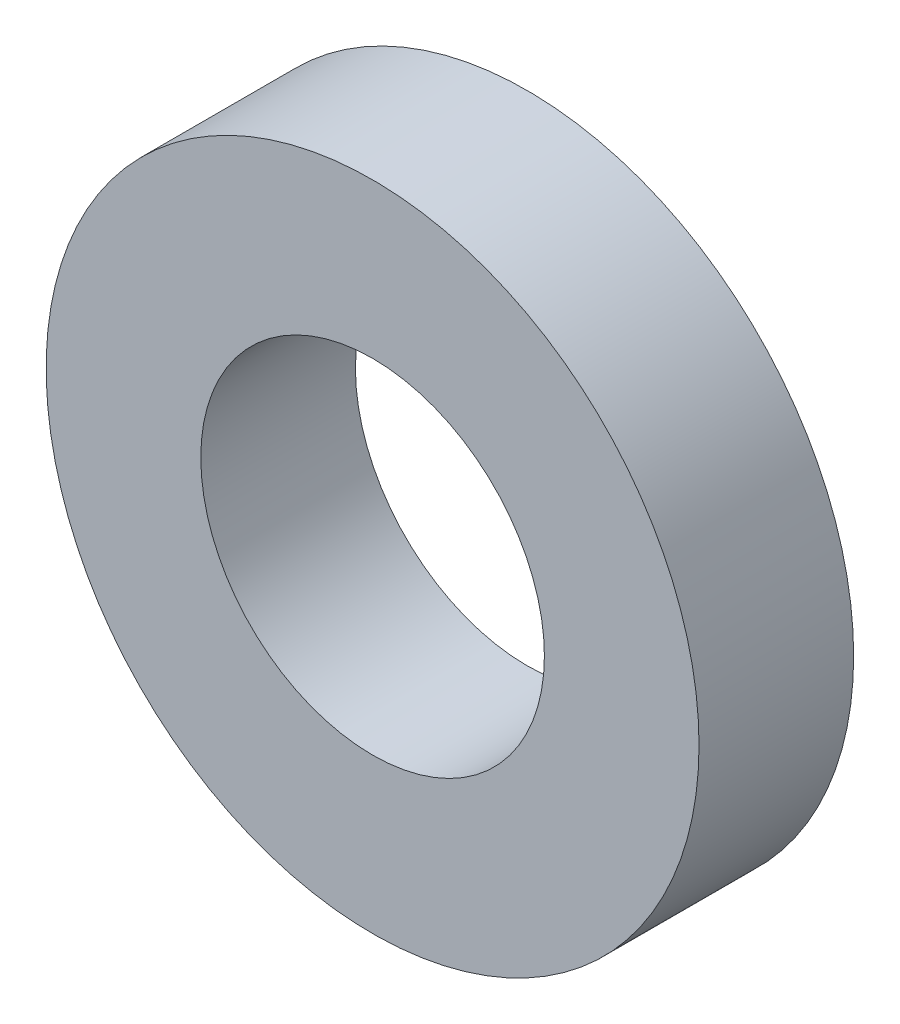
SolidWorks part; units mm, degrees
ref_plane "Front Plane" through (0, 0, 0) normal (0, 0, 1) x (1, 0, 0)
ref_plane "Top Plane" through (0, 0, 0) normal (0, 1, 0) x (1, 0, 0)
ref_plane "Right Plane" through (0, 0, 0) normal (1, 0, 0) x (0, 0, -1)
sketch "Sketch1" plane through (0, 0, 0) normal (0, 0, 1) x (1, 0, 0)
  circle A0 centre (0, 0) radius 9.5
  circle A1 centre (0, 0) radius 5
  dimension "D1" = 19
  dimension "D2" = 10
extrude "Boss-Extrude1" add sketch "Sketch1" along normal mid plane 4.5
